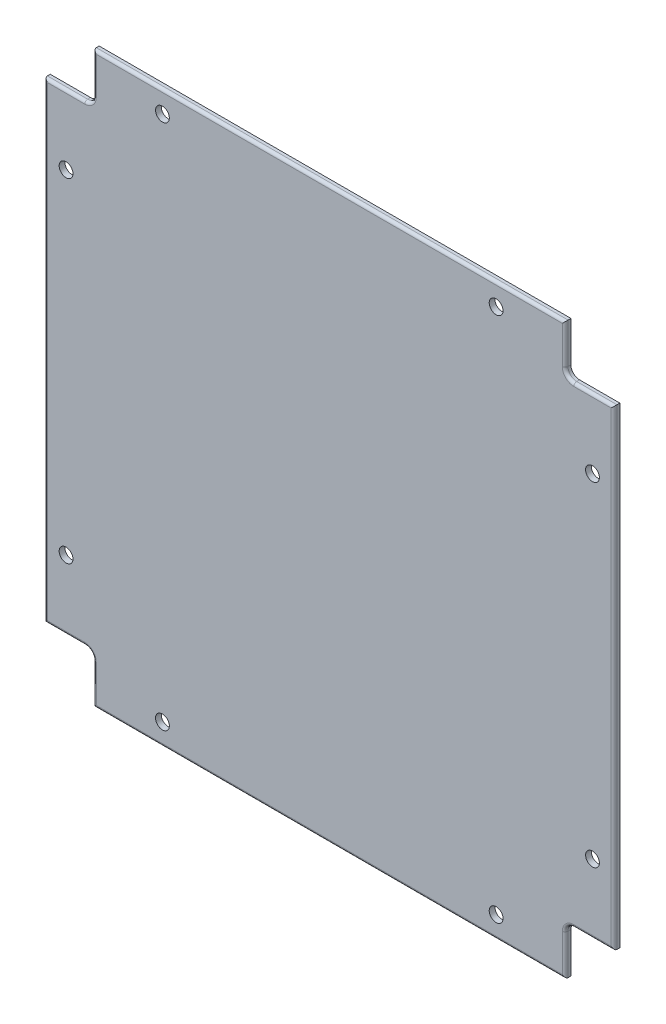
SolidWorks part; units mm, degrees
material "5052-H34"
ref_plane "Frontal" through (0, 0, 0) normal (0, 0, 1) x (1, 0, 0)
ref_plane "Superior" through (0, 0, 0) normal (0, 1, 0) x (1, 0, 0)
ref_plane "Direito" through (0, 0, 0) normal (1, 0, 0) x (0, 0, -1)
sketch "Sketch1" plane through (0, 0, 0) normal (0, 0, 1) x (1, 0, 0)
  line L1 (-49.5, -49.5) -> (49.5, -49.5)
  line L2 (-49.5, -49.5) -> (-49.5, 49.5)
  line L3 (-49.5, 49.5) -> (49.5, 49.5)
  line L4 (49.5, -49.5) -> (49.5, 49.5)
  line L5 (-49.5, -49.5) -> (49.5, 49.5) construction
  line L6 (-49.5, 49.5) -> (49.5, -49.5) construction
  point P0 (0, 0)
  dimension "D1" = 99
  dimension "D2" = 99
extrude "Boss-Extrude1" add sketch "Sketch1" along normal mid plane 1
sketch "Sketch2" plane through (0, 0, 0.5) normal (0, 0, 1) x (1, 0, 0)
  line L0 (-49.5, 49.5) -> (-49.5, -49.5) construction
  line L1 (-49.5, 49.5) -> (-41, 49.5)
  line L2 (-49.5, 49.5) -> (-49.5, 41)
  line L3 (-49.5, 41) -> (-42.5, 41)
  line L4 (-41, 49.5) -> (-41, 42.5)
  line L5 (49.5, 49.5) -> (41, 49.5)
  line L6 (49.5, 49.5) -> (49.5, 41)
  line L7 (49.5, 41) -> (42.5, 41)
  line L8 (41, 49.5) -> (41, 42.5)
  line L9 (-49.5, -49.5) -> (-41, -49.5)
  line L10 (-49.5, -49.5) -> (-49.5, -41)
  line L11 (-49.5, -41) -> (-42.5, -41)
  line L12 (-41, -49.5) -> (-41, -42.5)
  line L13 (49.5, -49.5) -> (41, -49.5)
  line L14 (49.5, -49.5) -> (49.5, -41)
  line L15 (49.5, -41) -> (42.5, -41)
  line L16 (41, -49.5) -> (41, -42.5)
  arc A0 (-41, 42.5) -> (-42.5, 41) centre (-42.5, 42.5) cw
  arc A1 (41, 42.5) -> (42.5, 41) centre (42.5, 42.5) ccw
  arc A2 (42.5, -41) -> (41, -42.5) centre (42.5, -42.5) ccw
  arc A3 (-42.5, -41) -> (-41, -42.5) centre (-42.5, -42.5) cw
  dimension "D1" = 1.5
  dimension "D3" = 1.5
  dimension "D5" = 1.5
  dimension "D7" = 1.5
  dimension "D2" = 8.5
  dimension "D4" = 8.5
  dimension "D6" = 8.5
  dimension "D8" = 8.5
  dimension "D9" = 8.5
  dimension "D10" = 8.5
  dimension "D11" = 8.5
  dimension "D12" = 8.5
extrude "Cut-Extrude1" cut sketch "Sketch2" against normal through all
hole_wizard "M2 Hole1 - B" positions "Sketch4" profile "Sketch3" hole size "M2" standard "DIN"
sketch "Sketch4" plane through (0, 0, 0.5) normal (0, 0, 1) x (1, 0, 0)
  line L0 (-41, 42.5) -> (-41, 49.5) construction
  line L1 (41, 49.5) -> (-41, 49.5) construction
  line L2 (41, 49.5) -> (41, 42.5) construction
  line L3 (-49.5, 41) -> (-49.5, -41) construction
  line L4 (-49.5, 41) -> (-42.5, 41) construction
  line L5 (-42.5, -41) -> (-49.5, -41) construction
  line L6 (49.5, -41) -> (49.5, 41) construction
  line L7 (-41, -49.5) -> (41, -49.5) construction
  point P0 (-45.75, 29)
  point P2 (-29, 45.75)
  point P4 (29, 45.75)
  point P6 (45.75, 29)
  point P8 (45.75, -29)
  point P10 (29, -45.75)
  point P12 (-29, -45.75)
  point P14 (-45.75, -29)
  dimension "D1" = 12
  dimension "D2" = 3.75
  dimension "D3" = 12
  dimension "D4" = 3.75
  dimension "D5" = 12
  dimension "D6" = 12
  dimension "D7" = 3.75
  dimension "D8" = 3.75
sketch "Sketch3" plane through (-45.75, 29, 0.5) normal (1, 0, 0) x (0, -1, 0)
  line L0 (0, 0) -> (0, 3.721)
  line L1 (0, 3.721) -> (1.2, 3)
  line L2 (1.2, 3) -> (1.2, 0)
  line L5 (1.2, 0) -> (0, 0)
  line L10 (0, 3.721) -> (-1.2, 3) construction
  line L11 (0, -6.35) -> (0, 107.95) construction
  dimension "Hole Dia." = 2.4
  dimension "Hole Depth" = 3
  dimension "Drill Angle" = 118
fillet "Fillet1" radius 0.5 16 edges at (41, 46, 0.5) (46, 41, 0.5) (49.5, 0, 0.5) (46, -41, 0.5) (41, -46, 0.5) (0, -49.5, 0.5) (-41, -46, 0.5) (-46, -41, 0.5) (-49.5, 0, 0.5) (-46, 41, 0.5) (-41, 46, 0.5) (0, 49.5, 0.5) (-41.4393, 41.4393, 0.5) (41.4393, 41.4393, 0.5) (41.4393, -41.4393, 0.5) (-41.4393, -41.4393, 0.5)
